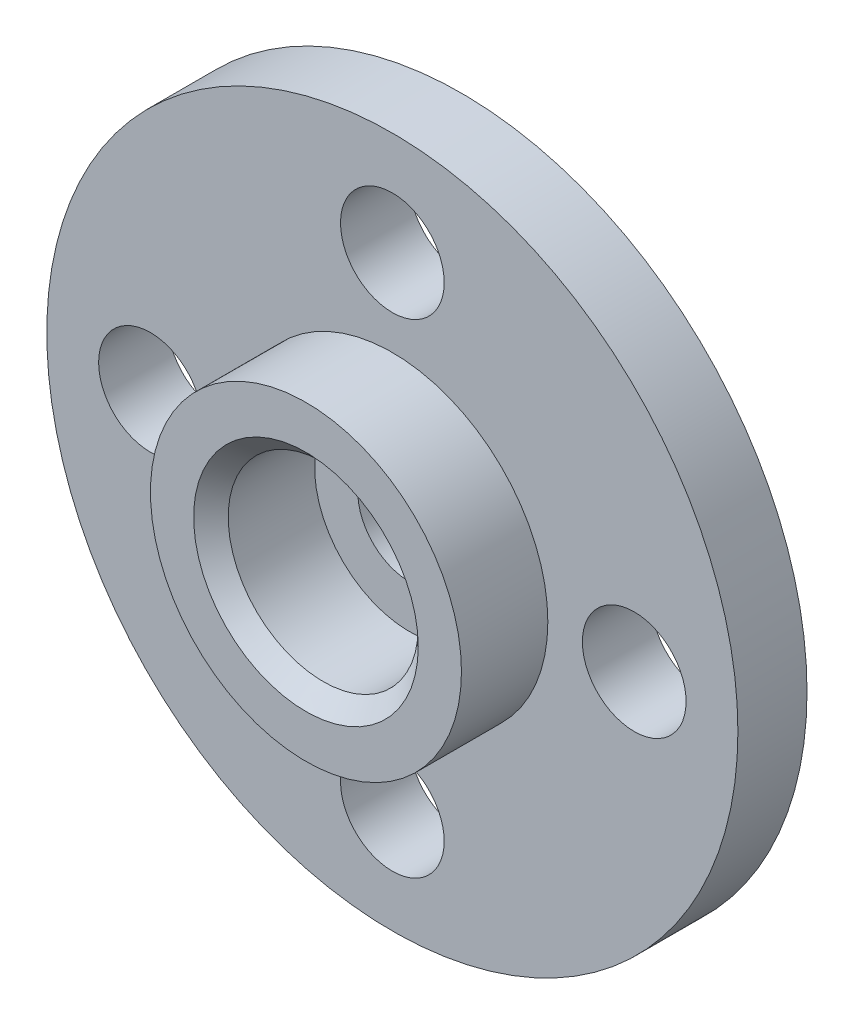
SolidWorks part; units mm, degrees
ref_plane "前视基准面" through (0, 0, 0) normal (0, 0, 1) x (1, 0, 0)
ref_plane "上视基准面" through (0, 0, 0) normal (0, 1, 0) x (1, 0, 0)
ref_plane "右视基准面" through (0, 0, 0) normal (1, 0, 0) x (0, 0, -1)
sketch "草图1" plane through (0, 0, 0) normal (0, 0, 1) x (1, 0, 0)
  circle A0 centre (0, 0) radius 10
  dimension "D1" = 20
extrude "凸台-拉伸1" add sketch "草图1" along normal blind 2
sketch "草图3" plane through (0, 0, 2) normal (0, 0, 1) x (1, 0, 0)
  circle A0 centre (0, 0) radius 4.5
extrude "凸台-拉伸2" add sketch "草图3" along normal blind 2.5
sketch "草图4" plane through (0, 0, 4.5) normal (0, 0, 1) x (1, 0, 0)
  circle A0 centre (0, 0) radius 1.5
  dimension "D1" = 3
extrude "切除-拉伸1" cut sketch "草图4" against normal through all
sketch "草图5" plane through (0, 0, 4.5) normal (0, 0, 1) x (1, 0, 0)
  circle A0 centre (0, 0) radius 2.75
  dimension "D1" = 5.5
extrude "切除-拉伸2" cut sketch "草图5" against normal blind 3
chamfer "倒角1" distance 0.5 angle 45 1 edges at (2.75, 0, 4.5)
sketch "草图6" plane through (0, 0, 0) normal (0, 0, -1) x (-1, 0, 0)
  line L0 (-12.0566, 0) -> (13.8191, 0) construction
  circle A0 centre (-7, 0) radius 1.5
  circle A1 centre (0, 7) radius 1.5
  circle A2 centre (7, 0) radius 1.5
  circle A3 centre (0, -7) radius 1.5
  point P14 (0, 0)
  dimension "D1" = 7
  dimension "D2" = 4
extrude "切除-拉伸3" cut sketch "草图6" against normal through all
